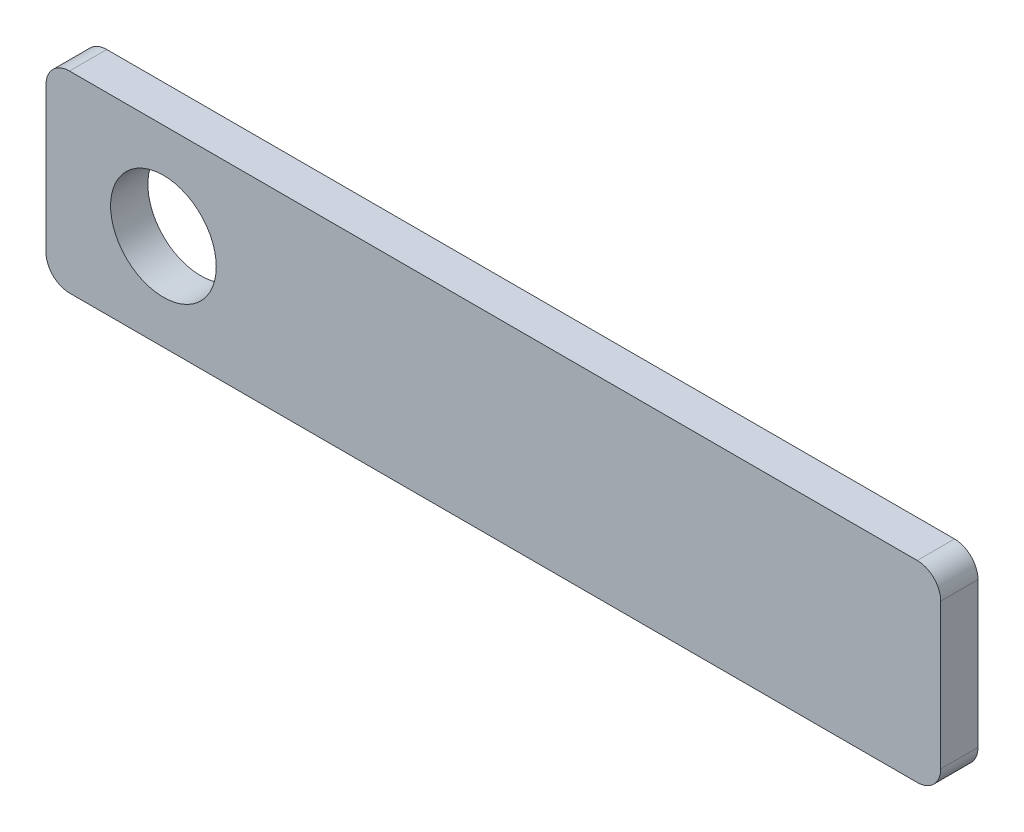
SolidWorks part; units mm, degrees
material "3003-H14"
ref_plane "X-Y Datum" through (0, 0, 0) normal (0, 0, 1) x (1, 0, 0)
ref_plane "X-Z Datum" through (0, 0, 0) normal (0, 1, 0) x (1, 0, 0)
ref_plane "Y-Z Datum" through (0, 0, 0) normal (1, 0, 0) x (0, 0, -1)
sketch "Sketch1" plane through (0, 0, 0) normal (0, 0, 1) x (1, 0, 0)
  line L0 (0, -8.189) -> (76.2, -8.189) construction
  line L1 (0, 0) -> (76.2, 0)
  line L2 (0, 0) -> (0, -16.378)
  line L3 (0, -16.378) -> (76.2, -16.378)
  line L4 (76.2, 0) -> (76.2, -16.378)
  circle A0 centre (10, -8.189) radius 4 construction
  dimension "D3" = 8
  dimension "D1" = 16.378
  dimension "D2" = 76.2
  dimension "D4" = 10
extrude "Boss-Extrude1" add sketch "Sketch1" along normal blind 3.175
fillet "Fillet1" radius 2 4 edges at (76.2, 0, 1.5875) (76.2, -16.378, 1.5875) (0, -16.378, 1.5875) (0, 0, 1.5875)
hole_wizard "M8 Clearance Hole1" positions "Sketch2" profile "Sketch3" hole size "M8" standard "ANSI Metric" end condition through all
sketch "Sketch2" plane through (0, 0, 3.175) normal (0, 0, 1) x (1, 0, 0)
  point P0 (10, -8.189)
sketch "Sketch3" plane through (10, -8.189, 3.175) normal (1, 0, 0) x (0, -1, 0)
  line L0 (0, 0) -> (0, 3.175)
  line L1 (0, 3.175) -> (4.5, 3.175)
  line L2 (4.5, 3.175) -> (4.5, 0)
  line L5 (4.5, 0) -> (0, 0)
  line L11 (0, -6.35) -> (0, 107.95) construction
  dimension "Thru Hole Dia." = 9
  dimension "Thru Hole Depth" = 3.175
